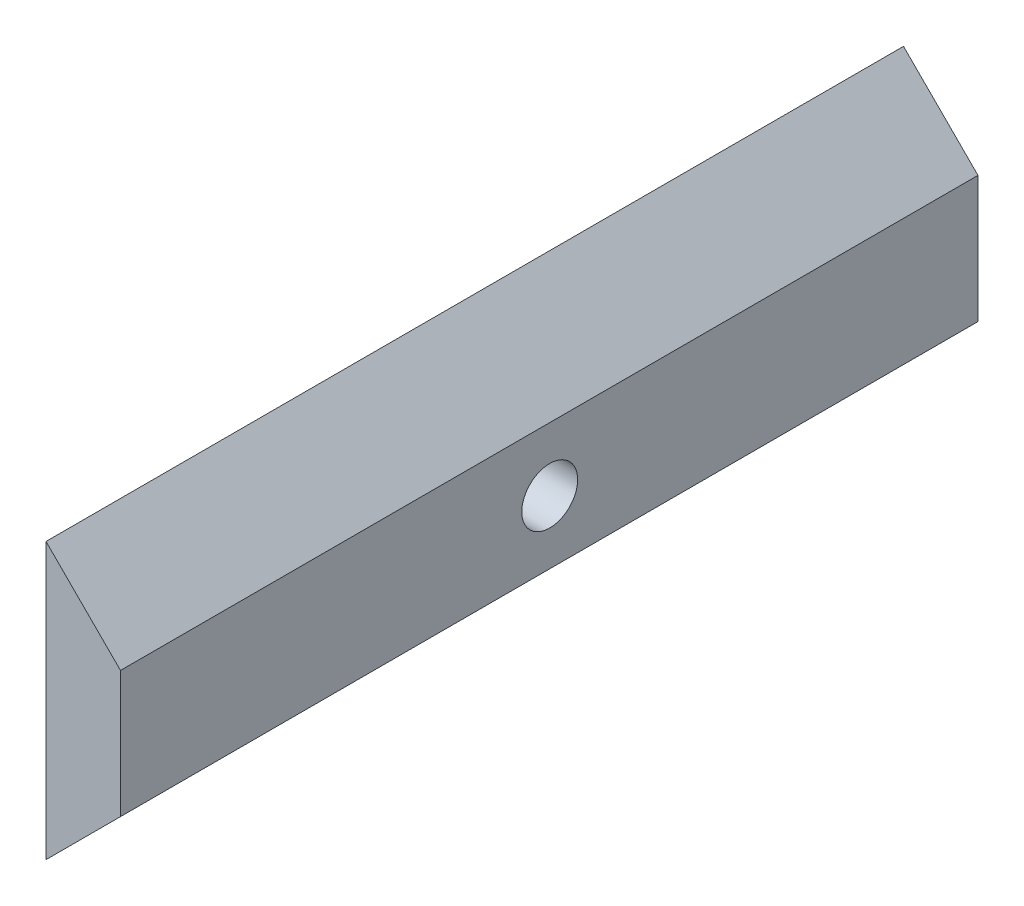
SolidWorks part; units mm, degrees
ref_plane "Front Plane" through (0, 0, 0) normal (0, 0, 1) x (1, 0, 0)
ref_plane "Top Plane" through (0, 0, 0) normal (0, 1, 0) x (1, 0, 0)
ref_plane "Right Plane" through (0, 0, 0) normal (1, 0, 0) x (0, 0, -1)
sketch "Sketch1" plane through (0, 0, 0) normal (0, 0, 1) x (1, 0, 0)
  line L0 (10.7466, -0.1027) -> (12.7466, 1.8973)
  line L2 (10.7466, 7.2973) -> (10.7466, -0.1027)
  line L4 (12.7466, 5.2973) -> (12.7466, 1.8973)
  line L5 (13.3466, 4.6973) -> (10.7466, 7.2973) construction
  line L6 (10.7466, 7.2973) -> (12.7466, 5.2973)
  line L7 (12.7466, 1.8973) -> (13.2466, 2.3973) construction
  line L8 (13.2466, 2.3973) -> (13.2466, 4.7973) construction
  line L11 (13.2466, 4.7973) -> (12.7466, 5.2973) construction
  line L14 (13.3466, 2.4973) -> (10.7466, -0.1027) construction
  dimension "D2" = 2
  dimension "D3" = 0.5
extrude "Boss-Extrude1" add sketch "Sketch1" along normal up to surface (73 mm away)
hole_wizard "Ø1.5mm Dowel Hole" positions "Sketch2" profile "Sketch3" hole size "Ø1.5" standard "ANSI Metric"
sketch "Sketch2" plane through (14.2466, -88.1027, 36.5) normal (1, 0, 0) x (0, 0, -1)
  point P0 (0, 91.7)
  point P3 (-25, 91.7)
  point P6 (25, 91.7)
sketch "Sketch3" plane through (14.2466, 3.5973, 36.5) normal (0, 1, 0) x (0, 0, -1)
  line L0 (0, 0) -> (0, 3.9496)
  line L1 (0, 3.9496) -> (0.75, 3.499)
  line L2 (0.75, 3.499) -> (0.75, 0)
  line L3 (0.75, 0) -> (0, 0)
  line L4 (0, 3.9496) -> (-0.75, 3.499) construction
  line L5 (0, -6.35) -> (0, 107.95) construction
  dimension "Hole Dia." = 1.5
  dimension "Hole Depth" = 3.499
  dimension "Drill Angle" = 118
